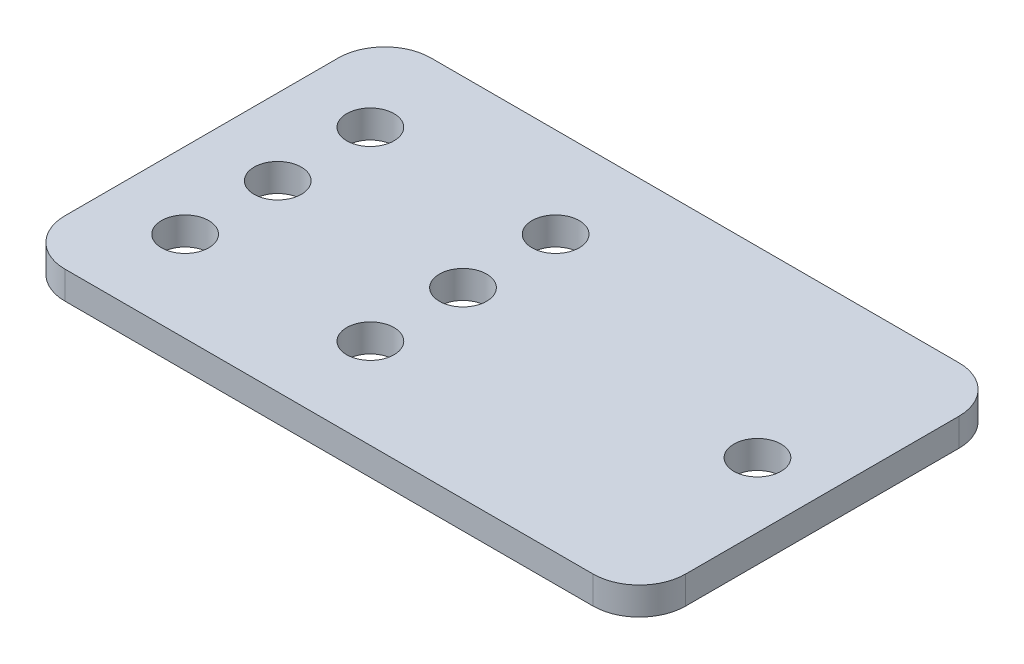
SolidWorks part; units mm, degrees
ref_plane "Front Plane" through (0, 0, 0) normal (0, 0, 1) x (1, 0, 0)
ref_plane "Top Plane" through (0, 0, 0) normal (0, 1, 0) x (1, 0, 0)
ref_plane "Right Plane" through (0, 0, 0) normal (1, 0, 0) x (0, 0, -1)
sketch "Sketch1" plane through (0, 0, 0) normal (0, 1, 0) x (1, 0, 0)
  line L1 (-5, 0) -> (-62, 0)
  line L2 (0, 5) -> (0, 34.5)
  line L3 (-5, 39.5) -> (-62, 39.5)
  line L4 (-67, 5) -> (-67, 34.5)
  circle A0 centre (-58.79, 29.75) radius 2.55
  circle A1 centre (-58.79, 19.75) radius 2.55
  circle A2 centre (-58.79, 9.75) radius 2.55
  arc A3 (-67, 5) -> (-62, 0) centre (-62, 5) ccw
  arc A4 (-5, 0) -> (0, 5) centre (-5, 5) ccw
  arc A5 (-5, 39.5) -> (0, 34.5) centre (-5, 34.5) cw
  arc A6 (-67, 34.5) -> (-62, 39.5) centre (-62, 34.5) cw
  circle A7 centre (-38.79, 29.75) radius 2.55
  circle A8 centre (-38.79, 19.75) radius 2.55
  circle A9 centre (-38.79, 9.75) radius 2.55
  circle A10 centre (-7, 19.75) radius 2.55
  point P15 (0, 0)
  dimension "D3" = 9.75
  dimension "D6" = 5
  dimension "D10" = 28.21
  dimension "D13" = 60
  dimension "D1" = 39.5
  dimension "D2" = 67
  dimension "D4" = 19.75
  dimension "D5" = 29.75
  dimension "D7" = 8.21
  dimension "D8" = 8.21
  dimension "D9" = 8.21
  dimension "D11" = 28.21
  dimension "D12" = 28.21
extrude "Boss-Extrude2" add sketch "Sketch1" along normal blind 3 contours A5 L3 A6 L4 A3 L1 A4 L2 | A9 | A8 | A2 | A1 | A0 | A7 | A10
